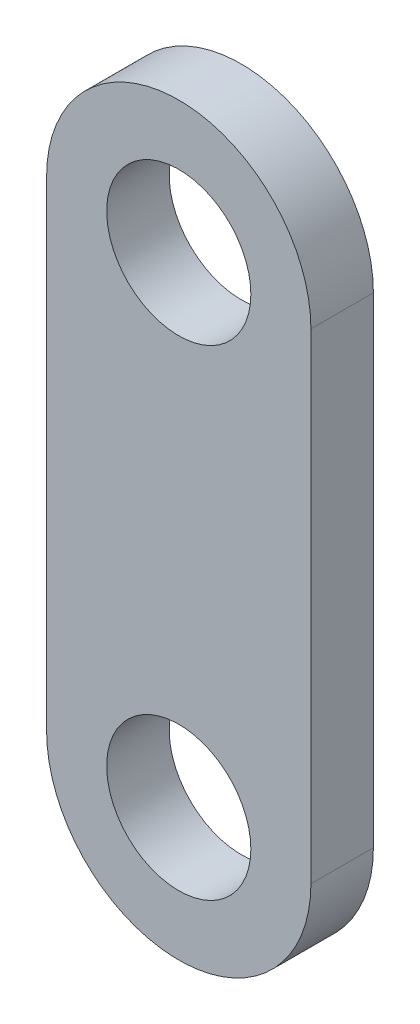
SolidWorks part; units mm, degrees
ref_plane "前视基准面" through (0, 0, 0) normal (0, 0, 1) x (1, 0, 0)
ref_plane "上视基准面" through (0, 0, 0) normal (0, 1, 0) x (1, 0, 0)
ref_plane "右视基准面" through (0, 0, 0) normal (1, 0, 0) x (0, 0, -1)
sketch "草图1" plane through (0, 0, 0) normal (0, 0, 1) x (1, 0, 0)
  line L0 (0, 10) -> (0, -10) construction
  line L1 (5.5, 10) -> (5.5, -10)
  line L2 (-5.5, 10) -> (-5.5, -10)
  arc A0 (5.5, 10) -> (-5.5, 10) centre (0, 10) ccw
  arc A1 (-5.5, -10) -> (5.5, -10) centre (0, -10) ccw
  circle A2 centre (0, -10) radius 3
  circle A3 centre (0, 10) radius 3
  point P2 (0, 0)
  dimension "D2" = 5.5
  dimension "D3" = 6
  dimension "D1" = 20
extrude "凸台-拉伸1" add sketch "草图1" along normal blind 2.6
